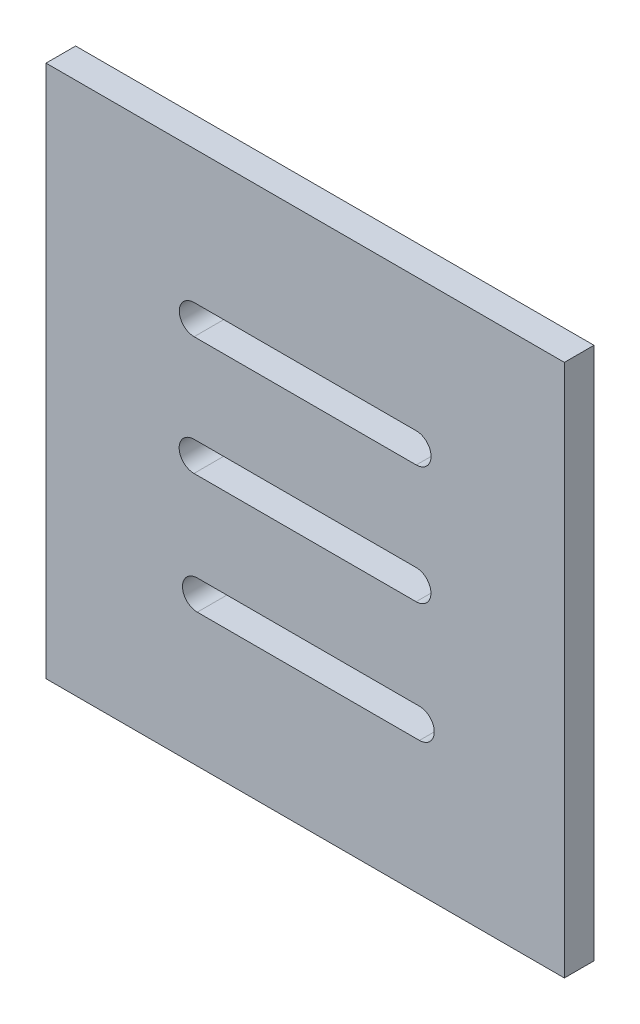
SolidWorks part; units mm, degrees
ref_plane "前视基准面" through (0, 0, 0) normal (0, 0, 1) x (1, 0, 0)
ref_plane "上视基准面" through (0, 0, 0) normal (0, 1, 0) x (1, 0, 0)
ref_plane "右视基准面" through (0, 0, 0) normal (1, 0, 0) x (0, 0, -1)
sketch "草图1" plane through (0, 0, 0) normal (0, 0, 1) x (1, 0, 0)
  line L1 (-17.5, 18) -> (17.5, 18)
  line L2 (-17.5, 18) -> (-17.5, -18)
  line L3 (-17.5, -18) -> (17.5, -18)
  line L4 (17.5, 18) -> (17.5, -18)
  line L5 (-17.5, 18) -> (17.5, -18) construction
  line L6 (-17.5, -18) -> (17.5, 18) construction
  point P0 (0, 0)
  dimension "D1" = 35
  dimension "D2" = 36
extrude "凸台-拉伸1" add sketch "草图1" along normal blind 2
sketch "草图2" plane through (0, 0, 2) normal (0, 0, 1) x (1, 0, 0)
  line L0 (-7.5, 8) -> (7.5, 8) construction
  line L1 (-7.5, 9) -> (7.5, 9)
  line L2 (-7.5, 7) -> (7.5, 7)
  line L3 (-17.5, 18) -> (-17.5, -18) construction
  line L4 (-7.5097, 0) -> (7.4903, 0) construction
  line L5 (-7.5097, 1) -> (7.4903, 1)
  line L6 (-7.5097, -1) -> (7.4903, -1)
  line L7 (-7.2853, -8) -> (7.7147, -8) construction
  line L8 (-7.2853, -7) -> (7.7147, -7)
  line L9 (-7.2853, -9) -> (7.7147, -9)
  line L11 (17.5, 18) -> (-17.5, 18) construction
  arc A0 (-7.5, 9) -> (-7.5, 7) centre (-7.5, 8) ccw
  arc A1 (7.5, 7) -> (7.5, 9) centre (7.5, 8) ccw
  arc A2 (-7.5097, 1) -> (-7.5097, -1) centre (-7.5097, 0) ccw
  arc A3 (7.4903, -1) -> (7.4903, 1) centre (7.4903, 0) ccw
  arc A4 (-7.2853, -7) -> (-7.2853, -9) centre (-7.2853, -8) ccw
  arc A5 (7.7147, -9) -> (7.7147, -7) centre (7.7147, -8) ccw
  point P2 (0, 8)
  point P7 (0, 0)
  point P12 (-0.0097, 0)
  point P20 (0.2147, -8)
  point P25 (0.8539, 18)
  dimension "D2" = 1
  dimension "D4" = 1
  dimension "D6" = 1
  dimension "D1" = 15
  dimension "D3" = 17.5
  dimension "D5" = 8
  dimension "D7" = 10
  dimension "D8" = 8
extrude "切除-拉伸1" cut sketch "草图2" against normal up to next
